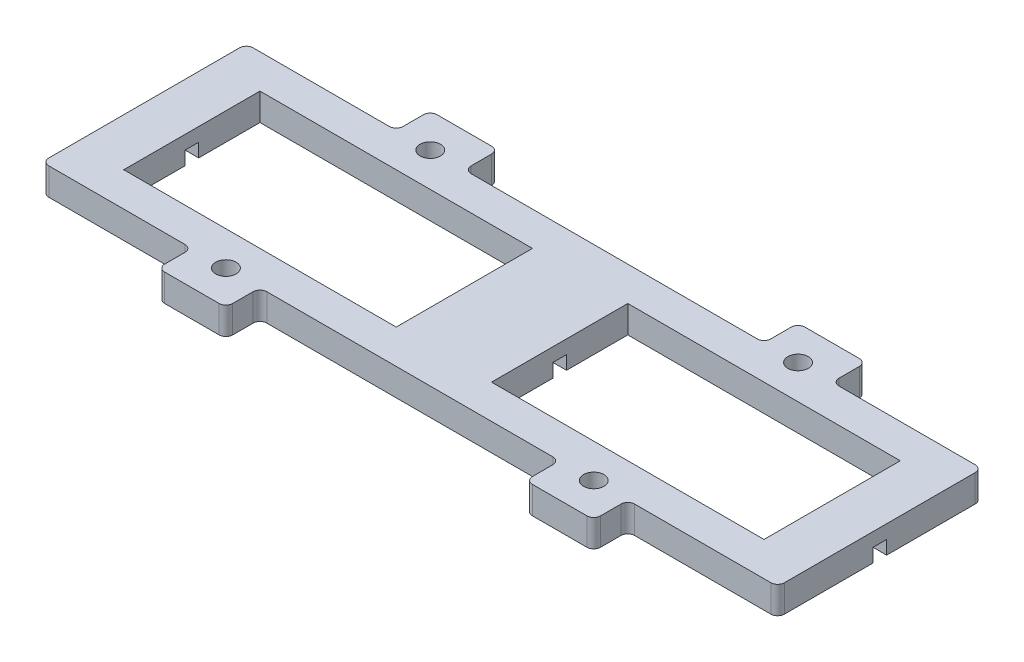
SolidWorks part; units mm, degrees
material "ABS"
ref_plane "前视基准面" through (0, 0, 0) normal (0, 0, 1) x (1, 0, 0)
ref_plane "上视基准面" through (0, 0, 0) normal (0, 1, 0) x (1, 0, 0)
ref_plane "右视基准面" through (0, 0, 0) normal (1, 0, 0) x (0, 0, -1)
sketch "草图2" plane through (0, 0, 0) normal (0, 1, 0) x (1, 0, 0)
  line L0 (0, 40.8185) -> (0, -34.2364) construction
  line L1 (-54, -15) -> (54, -15)
  line L2 (-54, -15) -> (-54, 15)
  line L3 (-54, 15) -> (54, 15)
  line L4 (54, -15) -> (54, 15)
  line L5 (-54, -15) -> (54, 15) construction
  line L6 (-54, 15) -> (54, -15) construction
  line L11 (-69.6601, 0) -> (82.6723, 0) construction
  line L12 (-32, 15) -> (-32, 20)
  line L13 (-27, 42.0153) -> (-27, -32.6977) construction
  line L14 (-32, 20) -> (-22, 20)
  line L15 (-22, 20) -> (-22, 15)
  line L16 (22, 20) -> (22, 15)
  line L17 (32, 15) -> (32, 20)
  line L18 (32, 20) -> (22, 20)
  line L19 (32, -15) -> (32, -20)
  line L20 (22, -20) -> (22, -15)
  line L21 (32, -20) -> (22, -20)
  line L22 (-22, -20) -> (-22, -15)
  line L23 (-32, -15) -> (-32, -20)
  line L24 (-32, -20) -> (-22, -20)
  point P0 (0, 0)
  point P5 (0, 0)
  dimension "D1" = 108
  dimension "D2" = 30
  dimension "D3" = 27
  dimension "D4" = 5
  dimension "D5" = 10
extrude "凸台-拉伸1" add sketch "草图2" along normal blind 4 contours L17 L18 L16 L3 | L15 L14 L12 L3 | L23 L24 L22 L1 | L21 L19 L1 L20 | L1 L4 L3 L2
sketch "草图3" plane through (0, 0, 0) normal (0, -1, 0) x (1, 0, 0)
  line L1 (-47, -10) -> (47, -10)
  line L2 (-47, -10) -> (-47, 10)
  line L3 (-47, 10) -> (47, 10)
  line L4 (47, -10) -> (47, 10)
  line L5 (-47, -10) -> (47, 10) construction
  line L6 (-47, 10) -> (47, -10) construction
  line L7 (0, 30.8679) -> (0, -25.1811) construction
  line L8 (-61.0229, 0) -> (67.1732, 0) construction
  line L9 (-32, 20) -> (-22, 20) construction
  line L10 (-22, 20) -> (-22, 15) construction
  circle A0 centre (-27, 15) radius 1.5
  circle A1 centre (27, 15) radius 1.5
  circle A2 centre (27, -15) radius 1.5
  circle A3 centre (-27, -15) radius 1.5
  point P0 (0, 0)
  dimension "D3" = 5
  dimension "D4" = 3
  dimension "D5" = 5
  dimension "D1" = 20
  dimension "D2" = 94
extrude "切除-拉伸1" cut sketch "草图3" against normal through all
fillet "圆角1" radius 1 20 edges at (-54, 2, -15) (-32, 2, -20) (-32, 2, -15) (-22, 2, -20) (-22, 2, -15) (22, 2, -15) (22, 2, -20) (32, 2, -20) (32, 2, -15) (54, 2, -15) (54, 2, 15) (32, 2, 15) (32, 2, 20) (22, 2, 20) (22, 2, 15) (-32, 2, 15) (-22, 2, 20) (-22, 2, 15) (-32, 2, 20) (-54, 2, 15)
sketch "草图4" plane through (0, 0, 0) normal (0, 1, 0) x (1, 0, 0)
  line L0 (0, -29.6711) -> (0, 39.863) construction
  line L1 (-63.1731, 0) -> (68.6547, 0) construction
  line L2 (47, -10) -> (-47, -10) construction
  line L3 (-7, 10) -> (7, 10)
  line L4 (-7, 10) -> (-7, -10)
  line L5 (-7, -10) -> (7, -10)
  line L6 (7, 10) -> (7, -10)
  line L7 (-7, 10) -> (7, -10) construction
  line L8 (-7, -10) -> (7, 10) construction
  point P4 (0, 0)
  dimension "D1" = 14
extrude "凸台-拉伸2" add sketch "草图4" along normal blind 4
sketch "草图6" plane through (0, 0, 0) normal (0, -1, 0) x (1, 0, 0)
  line L0 (-66.2744, 0) -> (68.4586, 0) construction
  line L1 (-54, 1) -> (-47, 1)
  line L2 (-54, 14) -> (-54, -14) construction
  line L3 (-47, 10) -> (-47, -10) construction
  line L4 (-47, 1) -> (-47, -1)
  line L5 (-47, -1) -> (-54, -1)
  line L6 (-54, -1) -> (-54, 1)
  line L7 (-7, 1) -> (7, 1)
  line L8 (-7, -10) -> (-7, 10) construction
  line L9 (7, 10) -> (7, -10) construction
  line L10 (7, 1) -> (7, -1)
  line L11 (7, -1) -> (-7, -1)
  line L12 (-7, -1) -> (-7, 1)
  line L13 (47, 1) -> (54, 1)
  line L14 (47, -10) -> (47, 10) construction
  line L15 (54, 14) -> (54, -14) construction
  line L16 (54, 1) -> (54, -1)
  line L17 (54, -1) -> (47, -1)
  line L18 (47, -1) -> (47, 1)
  dimension "D1" = 2
extrude "切除-拉伸3" cut sketch "草图6" against normal blind 2
